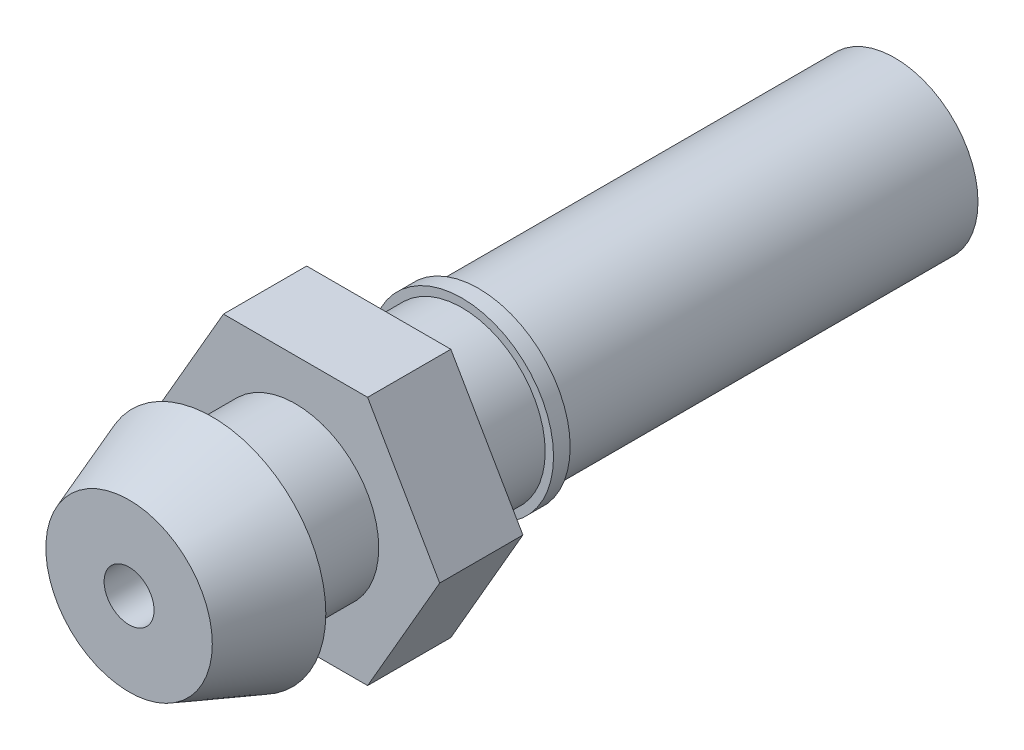
SolidWorks part; units mm, degrees
material "AISI Type 316L stainless steel"
ref_plane "Front Plane" through (0, 0, 0) normal (0, 0, 1) x (1, 0, 0)
ref_plane "Top Plane" through (0, 0, 0) normal (0, 1, 0) x (1, 0, 0)
ref_plane "Right Plane" through (0, 0, 0) normal (1, 0, 0) x (0, 0, -1)
sketch "Sketch1" plane through (0, 0, 0) normal (0, 0, 1) x (1, 0, 0)
  circle A0 centre (0, 0) radius 1.27
  dimension "D1" = 2.54
extrude "Boss-Extrude1" add sketch "Sketch1" along normal blind 6.35
sketch "Sketch2" plane through (0, 0, 6.35) normal (0, 0, 1) x (1, 0, 0)
  circle A0 centre (0, 0) radius 1.397
  dimension "D1" = 2.794
extrude "Boss-Extrude2" add sketch "Sketch2" along normal blind 0.254
sketch "Sketch3" plane through (0, 0, 6.604) normal (0, 0, 1) x (1, 0, 0)
  circle A0 centre (0, 0) radius 1.27
  dimension "D1" = 2.54
extrude "Boss-Extrude3" add sketch "Sketch3" along normal blind 1.27
sketch "Sketch4" plane through (0, 0, 7.874) normal (0, 0, 1) x (1, 0, 0)
  line L1 (2.1997, 0) -> (1.0999, 1.905)
  line L2 (1.0999, 1.905) -> (-1.0999, 1.905)
  line L3 (-1.0999, 1.905) -> (-2.1997, 0)
  line L4 (-2.1997, 0) -> (-1.0999, -1.905)
  line L5 (-1.0999, -1.905) -> (1.0999, -1.905)
  line L6 (1.0999, -1.905) -> (2.1997, 0)
  circle A0 centre (0, 0) radius 1.905 construction
  dimension "D1" = 3.81
extrude "Boss-Extrude4" add sketch "Sketch4" along normal blind 1.27
sketch "Sketch5" plane through (0, 0, 9.144) normal (0, 0, 1) x (1, 0, 0)
  circle A0 centre (0, 0) radius 1.27
  dimension "D1" = 2.54
extrude "Boss-Extrude5" add sketch "Sketch5" along normal blind 1.27
sketch "Sketch6" plane through (0, 0, 10.414) normal (0, 0, 1) x (1, 0, 0)
  circle A0 centre (0, 0) radius 1.27
  dimension "D1" = 2.54
extrude "Boss-Extrude6" add sketch "Sketch6" along normal blind 1.27 separate body
draft "Draft3" type of draft neutral plane draft angle 20 faces to draft 1 face at (1.27, 0, 11.684) neutral plane through (0, 0, 11.684) neutral plane normal (0, 0, 1) parameters "D1"=20
sketch "Sketch7" plane through (0, 0, 11.684) normal (0, 0, 1) x (1, 0, 0)
  circle A0 centre (0, 0) radius 0.381
  dimension "D1" = 0.762
extrude "Cut-Extrude1" cut sketch "Sketch7" against normal through all
move or copy body "Body-Move/Copy1" [suppressed] bodies to move or copy 107 108
